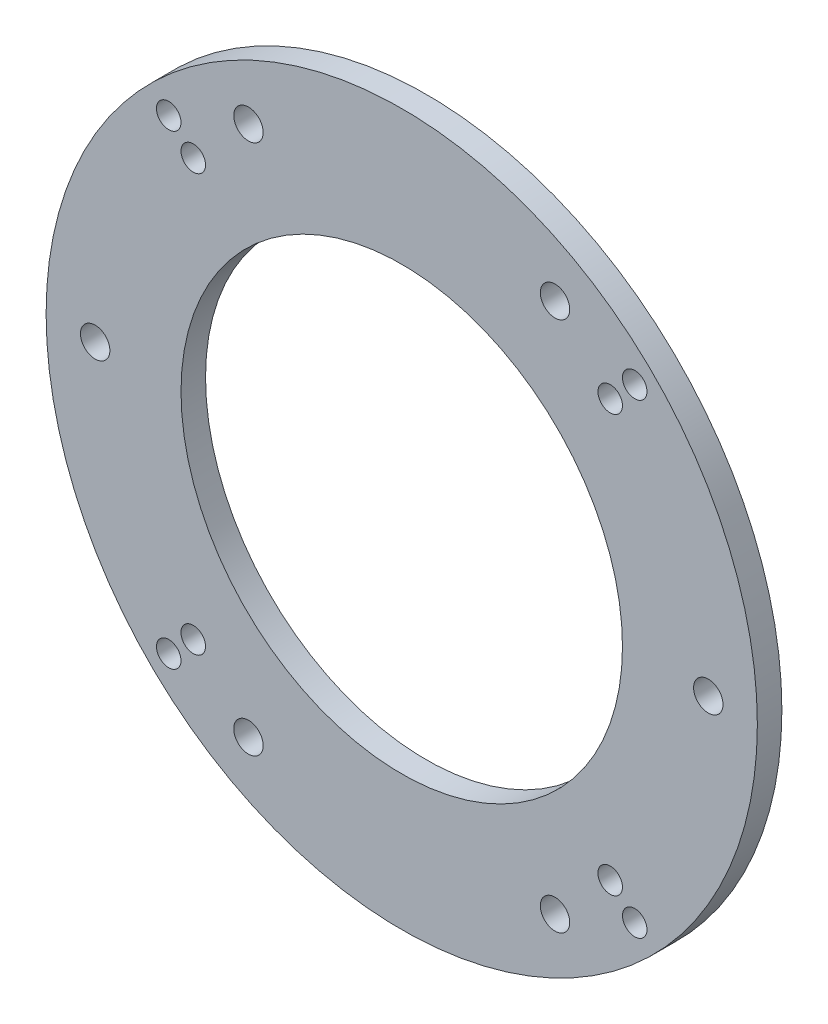
SolidWorks part; units mm, degrees
ref_plane "Front Plane" through (0, 0, 0) normal (0, 0, 1) x (1, 0, 0)
ref_plane "Top Plane" through (0, 0, 0) normal (0, 1, 0) x (1, 0, 0)
ref_plane "Right Plane" through (0, 0, 0) normal (1, 0, 0) x (0, 0, -1)
sketch "Sketch1" plane through (0, 0, 0) normal (0, 0, 1) x (1, 0, 0)
  line L4 (0, 39) -> (0, -40.7055) construction
  line L5 (-43.0364, 0) -> (51.1093, 0) construction
  arc A0 (-29, 0) -> (29, 0) centre (0, 0) ccw
  arc A1 (29, 0) -> (-29, 0) centre (0, 0) ccw
  circle A2 centre (0, 0) radius 18
  dimension "D1" = 58
  dimension "D4" = 36
extrude "Boss-Extrude1" add sketch "Sketch1" along normal blind 2
sketch "Sketch3" plane through (0, 0, 2) normal (0, 0, 1) x (1, 0, 0)
  line L0 (0, 15.6309) -> (0, -13.6849) construction
  line L1 (-12.5553, 0) -> (11.836, 0) construction
  point P5 (-17, 17)
  point P6 (17, 17)
  point P7 (17, -17)
  point P8 (-17, -17)
  point P9 (19, 19)
  point P10 (19, -19)
  point P11 (-19, -19)
  point P13 (-19, 19)
  dimension "D1" = 34
  dimension "D2" = 34
  dimension "D3" = 38
  dimension "D4" = 38
hole_wizard "Ø2.0mm Dowel Hole1" positions "3DSketch1" profile "Sketch4" hole size "Ø2.0" standard "ANSI Metric" end condition through all
sketch3d "3DSketch1"
  point P0 (-19, 19, 2)
  point P3 (-17, 17, 2)
  point P6 (17, 17, 2)
  point P9 (19, 19, 2)
  point P12 (17, -17, 2)
  point P15 (19, -19, 2)
  point P18 (-19, -19, 2)
  point P21 (-17, -17, 2)
sketch "Sketch4" plane through (-19, 19, 2) normal (1, 0, 0) x (0, -1, 0)
  line L0 (0, 0) -> (0, 2)
  line L1 (0, 2) -> (1, 2)
  line L2 (1, 2) -> (1, 0)
  line L5 (1, 0) -> (0, 0)
  line L11 (0, -6.35) -> (0, 107.95) construction
  dimension "Thru Hole Dia." = 2
  dimension "Thru Hole Depth" = 2
sketch "Sketch5" plane through (0, 0, 0) normal (0, 0, 1) x (1, 0, 0)
  line L0 (-12.5, 21.6506) -> (12.5, -21.6506) construction
  line L1 (12.5, -21.6506) -> (12.5, 21.6506) construction
  line L2 (12.5, 21.6506) -> (-25, 0) construction
  line L3 (-25, 0) -> (12.5, -21.6506) construction
  line L5 (-12.5, 21.6506) -> (-12.5, -21.6506) construction
  line L6 (-12.5, -21.6506) -> (25, 0) construction
  line L7 (25, 0) -> (-12.5, 21.6506) construction
  line L8 (12.5, 21.6506) -> (-12.5, -21.6506) construction
  line L9 (-25, 0) -> (25, 0) construction
  circle A0 centre (-12.5, 21.6506) radius 1.2
  circle A1 centre (-25, 0) radius 1.2
  circle A2 centre (25, 0) radius 1.2
  circle A3 centre (-12.5, -21.6506) radius 1.2
  circle A4 centre (12.5, 21.6506) radius 1.2
  circle A5 centre (12.5, -21.6506) radius 1.2
  dimension "D1" = 2.4
  dimension "D2" = 25
  dimension "D3" = 25
  dimension "D4" = 25
extrude "Cut-Extrude4" cut sketch "Sketch5" along normal through all
